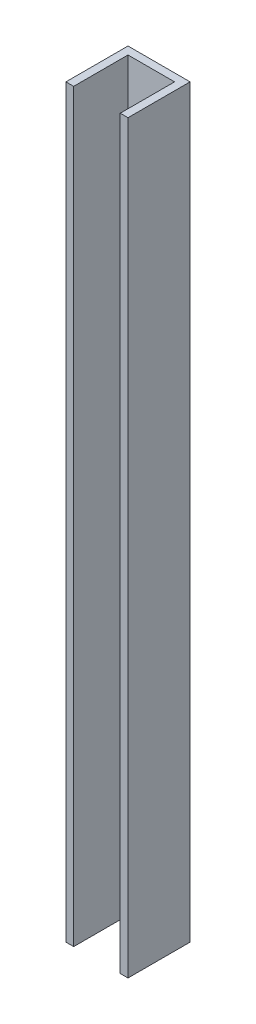
SolidWorks part; units mm, degrees
ref_plane "Front Plane" through (0, 0, 0) normal (0, 0, 1) x (1, 0, 0)
ref_plane "Top Plane" through (0, 0, 0) normal (0, 1, 0) x (1, 0, 0)
ref_plane "Right Plane" through (0, 0, 0) normal (1, 0, 0) x (0, 0, -1)
sketch "Sketch1" plane through (0, 0, 0) normal (0, 1, 0) x (1, 0, 0)
  line L0 (0, 0) -> (0, 25)
  line L1 (0, 25) -> (25, 25)
  line L2 (25, 25) -> (25, 0)
  line L3 (25, 0) -> (21.875, 0)
  line L4 (12.5, 25) -> (12.5, -14.119) construction
  line L5 (0, 0) -> (3.125, 0)
  line L6 (3.125, 0) -> (3.125, 21.875)
  line L7 (3.125, 21.875) -> (21.875, 21.875)
  line L8 (21.875, 21.875) -> (21.875, 0)
extrude "Boss-Extrude1" add sketch "Sketch1" along normal blind 300
